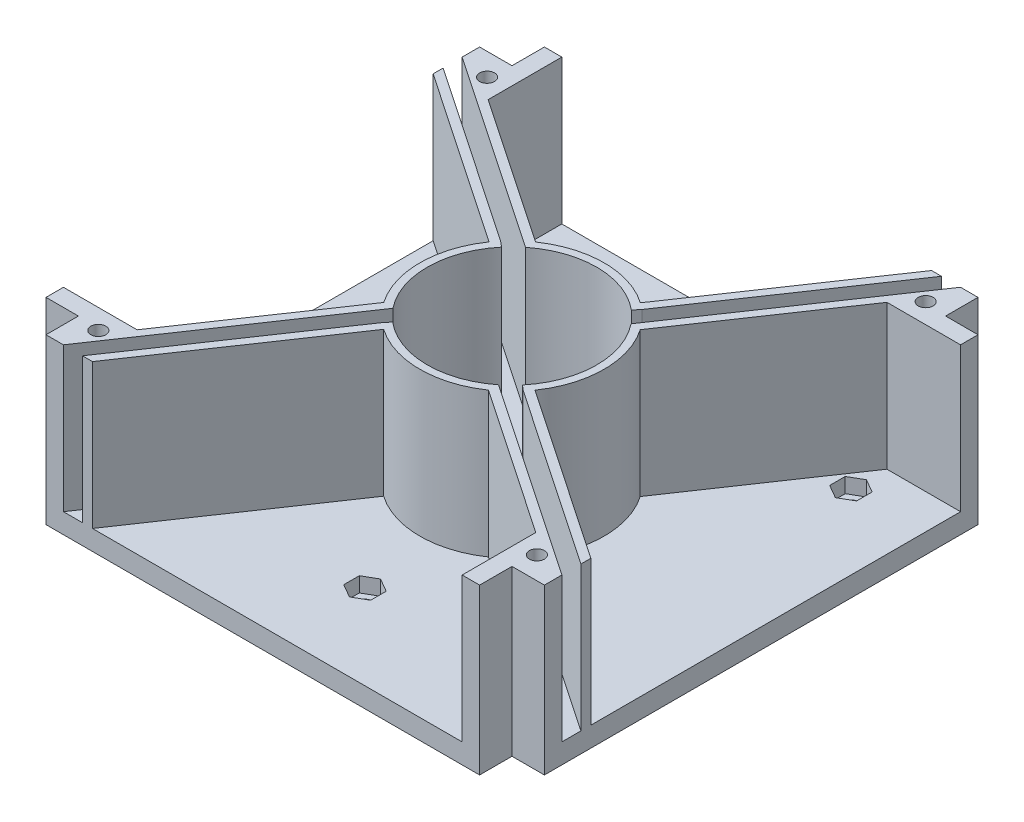
SolidWorks part; units mm, degrees
ref_plane "Front Plane" through (0, 0, 0) normal (0, 0, 1) x (1, 0, 0)
ref_plane "Top Plane" through (0, 0, 0) normal (0, 1, 0) x (1, 0, 0)
ref_plane "Right Plane" through (0, 0, 0) normal (1, 0, 0) x (0, 0, -1)
sketch "Sketch1" plane through (0, 0, 0) normal (0, 1, 0) x (1, 0, 0)
  line L0 (0, -50) -> (0, 50) construction
  line L1 (-50, 0) -> (50, 0) construction
  line L2 (-55, 0) -> (55, 0) construction
  line L3 (0, -55) -> (0, 55) construction
  line L5 (50, 50) -> (-50, 50)
  line L6 (50, 50) -> (50, -50)
  line L7 (50, -50) -> (-50, -50)
  line L8 (-50, 50) -> (-50, -50)
  point P10 (0, 0)
extrude "Boss-Extrude1" add sketch "Sketch1" along normal blind 4
sketch "Sketch2" plane through (0, 4, 0) normal (0, 1, 0) x (1, 0, 0)
  circle A0 centre (0, 0) radius 4.7625
extrude "Cut-Extrude1" cut sketch "Sketch2" against normal through all contours A0
sketch "Sketch3" plane through (0, 4, 0) normal (0, 1, 0) x (1, 0, 0)
  line L0 (0, -2.2) -> (0, 2.2) construction
  line L1 (-50, 50) -> (-41.5, 50)
  line L2 (-50, 50) -> (-50, 41.5)
  line L3 (-50, 41.5) -> (-41.5, 41.5)
  line L4 (-41.5, 50) -> (-41.5, 41.5)
  line L5 (50, 41.5) -> (41.5, 41.5)
  line L6 (41.5, 50) -> (41.5, 41.5)
  line L7 (50, 50) -> (41.5, 50)
  line L8 (50, 50) -> (50, 41.5)
  line L9 (-2.2, 0) -> (2.2, 0) construction
  line L10 (50, -50) -> (50, -41.5)
  line L11 (50, -50) -> (41.5, -50)
  line L12 (41.5, -50) -> (41.5, -41.5)
  line L13 (50, -41.5) -> (41.5, -41.5)
  line L14 (-50, -41.5) -> (-41.5, -41.5)
  line L15 (-41.5, -50) -> (-41.5, -41.5)
  line L16 (-50, -50) -> (-41.5, -50)
  line L17 (-50, -50) -> (-50, -41.5)
extrude "Cut-Extrude2" cut sketch "Sketch3" against normal through all
sketch "Sketch4" plane through (0, 4, 0) normal (0, 1, 0) x (1, 0, 0)
  line L0 (0, -2.2) -> (0, 2.2) construction
  line L1 (-10.9274, -13.0228) -> (-11.8916, -14.1718)
  line L2 (10.9274, -13.0228) -> (11.8916, -14.1718)
  line L3 (-13.0228, -10.9274) -> (-14.1718, -11.8916)
  line L4 (-13.0228, 10.9274) -> (-14.1718, 11.8916)
  line L5 (-10.9274, 13.0228) -> (-11.8916, 14.1718)
  line L6 (10.9274, 13.0228) -> (11.8916, 14.1718)
  line L7 (13.0228, 10.9274) -> (14.1718, 11.8916)
  line L8 (13.0228, -10.9274) -> (14.1718, -11.8916)
  line L9 (0, 0) -> (0, -17) construction
  circle A0 centre (0, 0) radius 17 construction
  arc A2 (-10.9274, -13.0228) -> (10.9274, -13.0228) centre (0, 0) ccw
  arc A3 (-11.8916, -14.1718) -> (11.8916, -14.1718) centre (0, 0) ccw
  arc A4 (-13.0228, 10.9274) -> (-13.0228, -10.9274) centre (0, 0) ccw
  arc A5 (-14.1718, 11.8916) -> (-14.1718, -11.8916) centre (0, 0) ccw
  arc A6 (10.9274, 13.0228) -> (-10.9274, 13.0228) centre (0, 0) ccw
  arc A7 (11.8916, 14.1718) -> (-11.8916, 14.1718) centre (0, 0) ccw
  arc A8 (13.0228, -10.9274) -> (13.0228, 10.9274) centre (0, 0) ccw
  arc A9 (14.1718, -11.8916) -> (14.1718, 11.8916) centre (0, 0) ccw
  dimension "D1" = 4
  dimension "D2" = 17
extrude "Boss-Extrude3" add sketch "Sketch4" along normal blind 29
sketch "Sketch7" plane through (0, 4, 0) normal (0, 1, 0) x (1, 0, 0)
  line L0 (-41.5, -41.5) -> (-41.5, -50)
  line L1 (-41.5, -50) -> (-40, -50)
  line L2 (-41.5, -50) -> (41.5, -50) construction
  line L3 (-41.5, -41.5) -> (-50, -41.5)
  line L4 (-50, -41.5) -> (-50, -40)
  line L5 (-50, 41.5) -> (-50, -41.5) construction
  line L6 (-40, -50) -> (-40, -40)
  line L7 (-40, -40) -> (-50, -40)
  line L8 (0, -18.15) -> (0, 18.15) construction
  line L9 (40, -50) -> (40, -40)
  line L10 (50, -41.5) -> (50, -40)
  line L11 (41.5, -41.5) -> (50, -41.5)
  line L12 (41.5, -41.5) -> (41.5, -50)
  line L13 (41.5, -50) -> (40, -50)
  line L14 (40, -40) -> (50, -40)
  line L15 (-18.15, 0) -> (18.15, 0) construction
  line L16 (50, 41.5) -> (50, 40)
  line L17 (40, 50) -> (40, 40)
  line L18 (40, 40) -> (50, 40)
  line L19 (41.5, 41.5) -> (50, 41.5)
  line L20 (41.5, 50) -> (40, 50)
  line L21 (41.5, 41.5) -> (41.5, 50)
  line L22 (-50, 41.5) -> (-50, 40)
  line L23 (-41.5, 41.5) -> (-50, 41.5)
  line L24 (-40, 40) -> (-50, 40)
  line L25 (-40, 50) -> (-40, 40)
  line L26 (-41.5, 50) -> (-40, 50)
  line L27 (-41.5, 41.5) -> (-41.5, 50)
extrude "Boss-Extrude4" add sketch "Sketch7" along normal blind 29
sketch "Sketch8" plane through (0, 4, 0) normal (0, 1, 0) x (1, 0, 0)
  line L11 (-14.1718, -11.8916) -> (-40, -50)
  line L12 (-11.8916, -14.1718) -> (-36.1743, -50)
  line L13 (-40, -50) -> (40, -50) construction
  line L14 (-36.1743, -50) -> (-40, -50)
  line L15 (-14.1718, -11.8916) -> (-12.4887, -9.4082)
  line L16 (-11.8916, -14.1718) -> (-9.8672, -11.1849)
  line L17 (-9.8672, -11.1849) -> (-12.4887, -9.4082)
  line L18 (-11.8916, 14.1718) -> (-50, 40)
  line L19 (-14.1718, 11.8916) -> (-50, 36.1743)
  line L20 (-50, 40) -> (-50, -40) construction
  line L21 (-50, 40) -> (-50, 36.1743)
  line L22 (-11.8916, 14.1718) -> (-9.4082, 12.4887)
  line L23 (-14.1718, 11.8916) -> (-11.1849, 9.8672)
  line L24 (-11.1849, 9.8672) -> (-9.4082, 12.4887)
  line L25 (14.1718, 11.8916) -> (40, 50)
  line L26 (11.8916, 14.1718) -> (36.1743, 50)
  line L27 (40, 50) -> (-40, 50) construction
  line L28 (36.1743, 50) -> (40, 50)
  line L29 (14.1718, 11.8916) -> (12.4887, 9.4082)
  line L30 (11.8916, 14.1718) -> (9.8672, 11.1849)
  line L31 (9.8672, 11.1849) -> (12.4887, 9.4082)
  line L32 (11.8916, -14.1718) -> (50, -40)
  line L33 (14.1718, -11.8916) -> (50, -36.1743)
  line L34 (50, -40) -> (50, 40) construction
  line L35 (50, -36.1743) -> (50, -40)
  line L36 (11.8916, -14.1718) -> (9.4082, -12.4887)
  line L37 (14.1718, -11.8916) -> (11.1849, -9.8672)
  line L38 (11.1849, -9.8672) -> (9.4082, -12.4887)
extrude "Cut-Extrude4" cut sketch "Sketch8" along normal through all
sketch "Sketch9" plane through (0, 4, 0) normal (0, 1, 0) x (1, 0, 0)
  line L0 (-11.8916, -14.1718) -> (-36.1743, -50)
  line L1 (-36.1743, -50) -> (-34.1743, -50)
  line L2 (-40, -50) -> (40, -50) construction
  line L5 (-14.1718, -11.8916) -> (-40, -50)
  line L6 (-34.1743, -50) -> (-10.5211, -15.1007)
  line L7 (-10.5211, -15.1007) -> (-11.8916, -14.1718)
  line L8 (-40, -50) -> (-42, -50) construction
  line L9 (-42, -50) -> (-40, -47.0491) construction
  line L10 (-40, -50) -> (-40, -40) construction
  line L11 (-40, -47.0491) -> (-14.9813, -10.1349)
  line L12 (-14.9813, -10.1349) -> (-13.6108, -11.0638)
  line L13 (-14.1718, -11.8916) -> (-12.4887, -9.4082) construction
  line L14 (-13.6108, -11.0638) -> (-14.1718, -11.8916)
  line L15 (-40, -47.0491) -> (-40, -50)
  line L16 (-50, 34.1743) -> (-15.1007, 10.5211)
  line L17 (-50, 36.1743) -> (-50, 34.1743)
  line L18 (-14.1718, 11.8916) -> (-50, 36.1743)
  line L19 (-11.8916, 14.1718) -> (-50, 40)
  line L20 (-47.0491, 40) -> (-10.1349, 14.9813)
  line L21 (-15.1007, 10.5211) -> (-14.1718, 11.8916)
  line L22 (-11.0638, 13.6108) -> (-11.8916, 14.1718)
  line L23 (-10.1349, 14.9813) -> (-11.0638, 13.6108)
  line L24 (-50, 42) -> (-47.0491, 40) construction
  line L25 (-50, 40) -> (-50, 42) construction
  line L26 (-47.0491, 40) -> (-50, 40)
  line L27 (34.1743, 50) -> (10.5211, 15.1007)
  line L28 (36.1743, 50) -> (34.1743, 50)
  line L29 (11.8916, 14.1718) -> (36.1743, 50)
  line L30 (14.1718, 11.8916) -> (40, 50)
  line L31 (40, 47.0491) -> (14.9813, 10.1349)
  line L32 (10.5211, 15.1007) -> (11.8916, 14.1718)
  line L33 (13.6108, 11.0638) -> (14.1718, 11.8916)
  line L34 (14.9813, 10.1349) -> (13.6108, 11.0638)
  line L35 (42, 50) -> (40, 47.0491) construction
  line L36 (40, 50) -> (42, 50) construction
  line L37 (40, 47.0491) -> (40, 50)
  line L38 (50, -34.1743) -> (15.1007, -10.5211)
  line L39 (50, -36.1743) -> (50, -34.1743)
  line L40 (14.1718, -11.8916) -> (50, -36.1743)
  line L41 (11.8916, -14.1718) -> (50, -40)
  line L42 (47.0491, -40) -> (10.1349, -14.9813)
  line L43 (15.1007, -10.5211) -> (14.1718, -11.8916)
  line L44 (11.0638, -13.6108) -> (11.8916, -14.1718)
  line L45 (10.1349, -14.9813) -> (11.0638, -13.6108)
  line L46 (50, -42) -> (47.0491, -40) construction
  line L47 (50, -40) -> (50, -42) construction
  line L48 (47.0491, -40) -> (50, -40)
  dimension "D1" = 1.6556
  dimension "D2" = 1.6556
  dimension "D3" = 4
extrude "Boss-Extrude5" add sketch "Sketch9" along normal blind 29
sketch "Sketch11" plane through (0, 4, 0) normal (0, 1, 0) x (1, 0, 0)
  line L0 (-40, -40) -> (-35.2225, -40)
  line L1 (-15.2301, -10.5021) -> (-40, -47.0491) construction
  line L2 (-35.2225, -40) -> (-40, -47.0491)
  line L3 (-40, -47.0491) -> (-40, -40)
  line L4 (-40, 40) -> (-40, 35.2225)
  line L5 (-47.0491, 40) -> (-40, 40)
  line L6 (-40, 35.2225) -> (-47.0491, 40)
  line L7 (40, 40) -> (35.2225, 40)
  line L8 (40, 47.0491) -> (40, 40)
  line L9 (35.2225, 40) -> (40, 47.0491)
  line L10 (40, -40) -> (40, -35.2225)
  line L11 (47.0491, -40) -> (40, -40)
  line L12 (40, -35.2225) -> (47.0491, -40)
  dimension "D1" = 4
extrude "Boss-Extrude6" add sketch "Sketch11" along normal blind 29
sketch "Sketch12" plane through (0, 0, 0) normal (0, -1, 0) x (-1, 0, 0)
  line L0 (0, 0) -> (-3.5, 0) construction
  line L1 (-3.5, 0) -> (-3.5, 33) construction
  line L2 (-3.5, 33) -> (-35, 33) construction
  line L3 (-18.15, 0) -> (18.15, 0) construction
  line L4 (-3.5, 0) -> (-3.5, -33) construction
  line L5 (-35, 33) -> (-35, -33) construction
  line L6 (-35, -33) -> (-28, -33) construction
  circle A0 centre (-3.5, 33) radius 1.5
  circle A3 centre (-3.5, -33) radius 1.5
  circle A6 centre (-35, 33) radius 1.5
  circle A7 centre (-28, -33) radius 1.5
extrude "Cut-Extrude5" cut sketch "Sketch12" against normal through all
sketch "Sketch14" plane through (0, 4, 0) normal (0, 1, 0) x (1, 0, 0)
  line L1 (28, -29.8823) -> (25.3, -31.4412)
  line L2 (25.3, -31.4412) -> (25.3, -34.5588)
  line L3 (25.3, -34.5588) -> (28, -36.1177)
  line L4 (28, -36.1177) -> (30.7, -34.5588)
  line L5 (30.7, -34.5588) -> (30.7, -31.4412)
  line L6 (30.7, -31.4412) -> (28, -29.8823)
  line L7 (3.5, -29.8823) -> (0.8, -31.4412)
  line L8 (0.8, -31.4412) -> (0.8, -34.5588)
  line L9 (0.8, -34.5588) -> (3.5, -36.1177)
  line L10 (3.5, -36.1177) -> (6.2, -34.5588)
  line L11 (6.2, -34.5588) -> (6.2, -31.4412)
  line L12 (6.2, -31.4412) -> (3.5, -29.8823)
  line L13 (3.5, 36.1177) -> (0.8, 34.5588)
  line L14 (0.8, 34.5588) -> (0.8, 31.4412)
  line L15 (0.8, 31.4412) -> (3.5, 29.8823)
  line L16 (3.5, 29.8823) -> (6.2, 31.4412)
  line L17 (6.2, 31.4412) -> (6.2, 34.5588)
  line L18 (6.2, 34.5588) -> (3.5, 36.1177)
  line L19 (35, 36.1177) -> (32.3, 34.5588)
  line L20 (32.3, 34.5588) -> (32.3, 31.4412)
  line L21 (32.3, 31.4412) -> (35, 29.8823)
  line L22 (35, 29.8823) -> (37.7, 31.4412)
  line L23 (37.7, 31.4412) -> (37.7, 34.5588)
  line L24 (37.7, 34.5588) -> (35, 36.1177)
  circle A0 centre (28, -33) radius 2.7 construction
  circle A1 centre (3.5, -33) radius 2.7 construction
  circle A2 centre (3.5, 33) radius 2.7 construction
  circle A3 centre (35, 33) radius 2.7 construction
extrude "Cut-Extrude6" cut sketch "Sketch14" against normal blind 3
sketch "Sketch15" plane through (0, 33, 0) normal (0, 1, 0) x (1, 0, 0)
  line L0 (41.5, -41.5) -> (41.5, -39) construction
  line L1 (41.5, -39) -> (44, -39) construction
  circle A0 centre (44, -39) radius 1.5
  circle A1 centre (-39, -44) radius 1.5
  circle A2 centre (-44, 39) radius 1.5
  circle A3 centre (39, 44) radius 1.5
  dimension "D1" = 4
extrude "Cut-Extrude7" cut sketch "Sketch15" against normal blind 10
sketch "Sketch16" plane through (0, 0, 0) normal (0, -1, 0) x (1, 0, 0)
  line L0 (-50, 41.5) -> (-50, 43.5)
  line L1 (-41.5, 50) -> (-43.5, 50)
  line L2 (-50, 43.5) -> (-43.5, 43.5)
  line L3 (-43.5, 43.5) -> (-43.5, 50)
  line L4 (-50, 41.5) -> (-41.5, 41.5)
  line L5 (-41.5, 41.5) -> (-41.5, 50)
  line L6 (0, -18.15) -> (0, 18.15) construction
  line L7 (50, 41.5) -> (41.5, 41.5)
  line L8 (50, 41.5) -> (50, 43.5)
  line L9 (50, 43.5) -> (43.5, 43.5)
  line L10 (43.5, 43.5) -> (43.5, 50)
  line L11 (41.5, 50) -> (43.5, 50)
  line L12 (41.5, 41.5) -> (41.5, 50)
  line L13 (18.15, 0) -> (-18.15, 0) construction
  line L14 (50, -41.5) -> (50, -43.5)
  line L15 (50, -43.5) -> (43.5, -43.5)
  line L16 (43.5, -43.5) -> (43.5, -50)
  line L17 (41.5, -50) -> (43.5, -50)
  line L18 (41.5, -41.5) -> (41.5, -50)
  line L19 (50, -41.5) -> (41.5, -41.5)
  line L20 (-50, -41.5) -> (-41.5, -41.5)
  line L21 (-50, -41.5) -> (-50, -43.5)
  line L22 (-50, -43.5) -> (-43.5, -43.5)
  line L23 (-43.5, -43.5) -> (-43.5, -50)
  line L24 (-41.5, -50) -> (-43.5, -50)
  line L25 (-41.5, -41.5) -> (-41.5, -50)
extrude "Boss-Extrude7" add sketch "Sketch16" against normal up to surface (33 mm away) up to face at (44, 33, 40.5)
scale "Scale1" bodies to scale 116 scale about centroid uniform scaling yes scale factor 0.95
